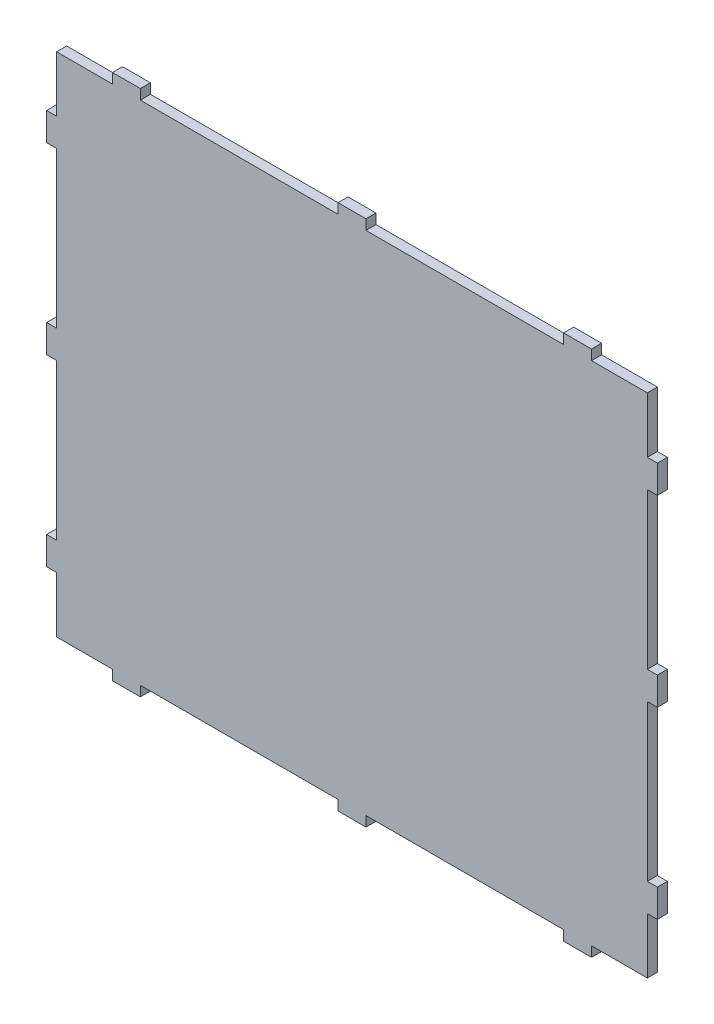
SolidWorks part; units mm, degrees
ref_plane "Front Plane" through (0, 0, 0) normal (0, 0, 1) x (1, 0, 0)
ref_plane "Top Plane" through (0, 0, 0) normal (0, 1, 0) x (1, 0, 0)
ref_plane "Right Plane" through (0, 0, 0) normal (1, 0, 0) x (0, 0, -1)
sketch "Sketch1" plane through (0, 0, 0) normal (0, 0, 1) x (1, 0, 0)
  line L0 (-961.2365, 328.9507) -> (-961.2365, 378.9507)
  line L8 (-943.2365, 807.9015) -> (-943.2365, 707.9015)
  line L9 (-943.2365, 707.9015) -> (-961.2365, 707.9015)
  line L10 (-961.2365, 657.9015) -> (-943.2365, 657.9015)
  line L11 (-943.2365, 657.9015) -> (-943.2365, 378.9507)
  line L12 (-943.2365, 378.9507) -> (-961.2365, 378.9507)
  line L13 (-961.2365, 657.9015) -> (-961.2365, 707.9015)
  line L18 (-414.1183, 825.9015) -> (-414.1183, 353.9507) construction
  line L19 (-961.2365, 353.9507) -> (-414.1183, 353.9507) construction
  line L20 (-943.2365, 807.9015) -> (-843.2365, 807.9015)
  line L21 (-843.2365, 807.9015) -> (-843.2365, 825.9015)
  line L22 (-843.2365, 825.9015) -> (-793.2365, 825.9015)
  line L23 (-793.2365, 825.9015) -> (-793.2365, 807.9015)
  line L24 (-793.2365, 807.9015) -> (-439.1183, 807.9015)
  line L25 (-439.1183, 807.9015) -> (-439.1183, 825.9015)
  line L26 (-843.2365, 603) -> (-843.2365, 0) construction
  line L28 (-439.1183, 825.9015) -> (-389.1183, 825.9015)
  line L29 (-788.166, 707.9015) -> (-779.041, 707.9015) construction
  line L30 (-439.1183, -118) -> (-389.1183, -118)
  line L31 (-439.1183, -100) -> (-439.1183, -118)
  line L32 (-793.2365, -100) -> (-439.1183, -100)
  line L33 (-793.2365, -118) -> (-793.2365, -100)
  line L34 (-843.2365, -118) -> (-793.2365, -118)
  line L35 (-843.2365, -100) -> (-843.2365, -118)
  line L36 (-943.2365, -100) -> (-843.2365, -100)
  line L37 (-961.2365, 50) -> (-961.2365, 0)
  line L38 (-943.2365, 328.9507) -> (-961.2365, 328.9507)
  line L39 (-943.2365, 50) -> (-943.2365, 328.9507)
  line L40 (-961.2365, 50) -> (-943.2365, 50)
  line L41 (-943.2365, 0) -> (-961.2365, 0)
  line L42 (-943.2365, -100) -> (-943.2365, 0)
  line L43 (-841.2365, 0) -> (-832.7445, 0) construction
  line L44 (115, -100) -> (115, 0)
  line L45 (115, 0) -> (133, 0)
  line L46 (133, 50) -> (115, 50)
  line L47 (115, 50) -> (115, 328.9507)
  line L48 (115, 328.9507) -> (133, 328.9507)
  line L49 (133, 50) -> (133, 0)
  line L50 (115, -100) -> (15, -100)
  line L51 (15, -100) -> (15, -118)
  line L52 (15, -118) -> (-35, -118)
  line L53 (-35, -118) -> (-35, -100)
  line L54 (-35, -100) -> (-389.1183, -100)
  line L55 (-389.1183, -100) -> (-389.1183, -118)
  line L56 (-389.1183, 807.9015) -> (-389.1183, 825.9015)
  line L57 (-35, 807.9015) -> (-389.1183, 807.9015)
  line L58 (-35, 825.9015) -> (-35, 807.9015)
  line L59 (15, 825.9015) -> (-35, 825.9015)
  line L60 (15, 807.9015) -> (15, 825.9015)
  line L61 (115, 807.9015) -> (15, 807.9015)
  line L62 (133, 657.9015) -> (133, 707.9015)
  line L63 (115, 378.9507) -> (133, 378.9507)
  line L64 (115, 657.9015) -> (115, 378.9507)
  line L65 (133, 657.9015) -> (115, 657.9015)
  line L66 (115, 707.9015) -> (133, 707.9015)
  line L67 (115, 807.9015) -> (115, 707.9015)
  line L68 (133, 328.9507) -> (133, 378.9507)
  line L69 (15, 603) -> (15, 0) construction
  point P24 (-961.2365, 353.9507)
  point P52 (-414.1183, -118)
  point P65 (133, 353.9507)
  dimension "D6" = 50
  dimension "D7" = 18
  dimension "D10" = 100
  dimension "D2" = 25
  dimension "D3" = 50
  dimension "D4" = 100
  dimension "D5" = 18
  dimension "D9" = 100
  dimension "D11" = 25
  dimension "D12" = 100
  dimension "D8" = 100
  dimension "D13" = 100
extrude "Boss-Extrude1" add sketch "Sketch1" along normal blind 18
equation "\"fingerlenght\"=50"
equation "\"D6@Sketch1\"=\"fingerlenght\""
equation "\"fingerendclearance\"=100"
equation "\"osbthickness\"=18"
equation "\"D7@Sketch1\"=\"osbthickness\""
equation "\"D2@Sketch1\"=\"fingerlenght\"/2"
equation "\"D3@Sketch1\"=\"fingerlenght\""
equation "\"D4@Sketch1\"=\"fingerendclearance\""
equation "\"D5@Sketch1\"=\"osbthickness\""
equation "\"D9@Sketch1\"=\"fingerendclearance\""
equation "\"D11@Sketch1\"=\"fingerlenght\"/2"
equation "\"wallclearance\"=100"
equation "\"D12@Sketch1\"=\"wallclearance\""
equation "\"D10@Sketch1\"=\"wallclearance\""
equation "\"D13@Sketch1\"=\"wallclearance\""
